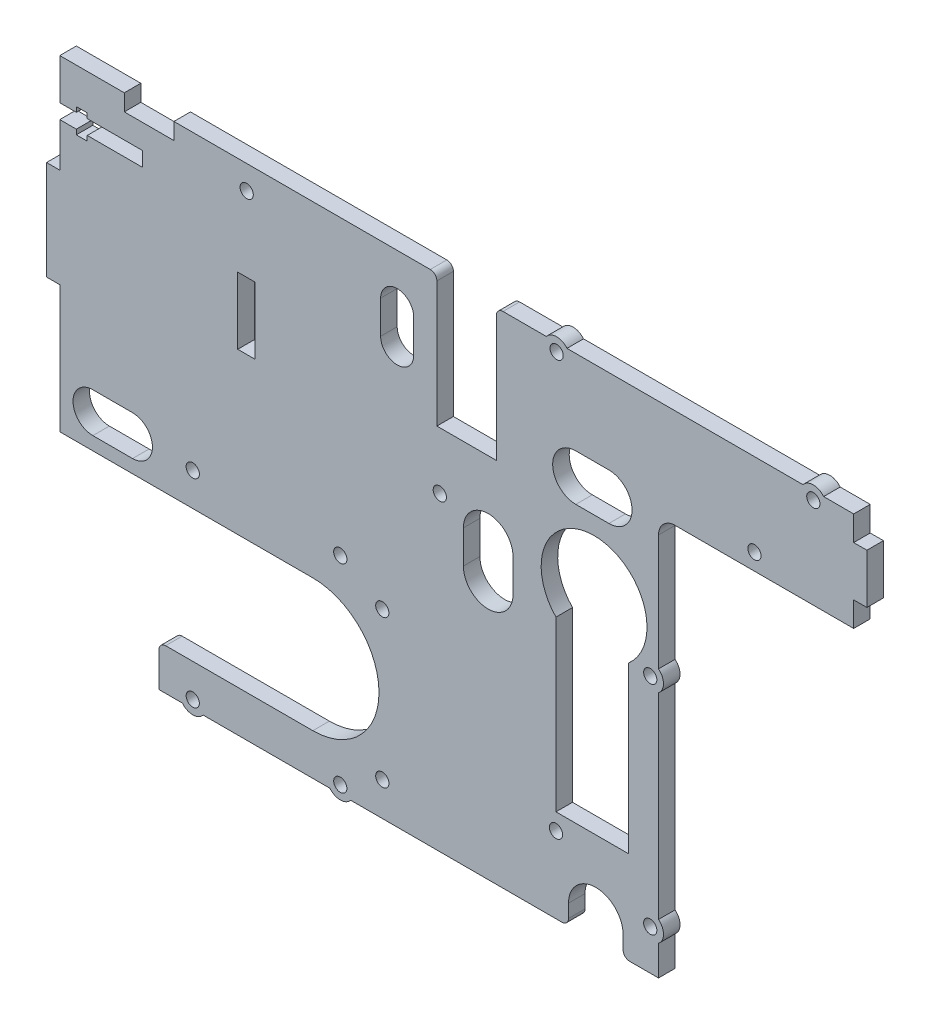
SolidWorks part; units mm, degrees
ref_plane "Front Plane" through (0, 0, 0) normal (0, 0, 1) x (1, 0, 0)
ref_plane "Top Plane" through (0, 0, 0) normal (0, 1, 0) x (1, 0, 0)
ref_plane "Right Plane" through (0, 0, 0) normal (1, 0, 0) x (0, 0, -1)
sketch "Sketch1" plane through (0, 0, 0) normal (0, 0, 1) x (1, 0, 0)
  line L1 (-120, 75.5) -> (120, 75.5)
  line L2 (-120, 75.5) -> (-120, -75.5)
  line L3 (-120, -75.5) -> (120, -75.5)
  line L4 (120, 75.5) -> (120, -75.5)
  dimension "D1" = 240
  dimension "D2" = 151
  dimension "D3" = 75.5
  dimension "D4" = 120
extrude "Boss-Extrude1" add sketch "Sketch1" along normal blind 5
sketch "Sketch5" plane through (0, 0, 0) normal (0, 0, -1) x (-1, 0, 0)
  line L0 (0, 0) -> (0, -52.2795) construction
  line L1 (0, 0) -> (58.5261, 0) construction
  line L3 (0, -43) -> (80.2371, -43) construction
  circle A1 centre (35.2, -73) radius 2
  circle A3 centre (79.8, -73) radius 2
  circle A5 centre (22.5, -65.3) radius 2
  circle A6 centre (22.5, -20.7) radius 2
  circle A7 centre (79.8, -13) radius 2
  circle A8 centre (35.2, -13) radius 2
  dimension "D5" = 44.6
  dimension "D6" = 4
  dimension "D7" = 4
  dimension "D8" = 4
  dimension "D1" = 22.5
  dimension "D2" = 65.3
  dimension "D3" = 35.2
  dimension "D4" = 73
  dimension "D9" = 43
extrude "Cut-Extrude1" cut sketch "Sketch5" against normal blind 5
sketch "Sketch6" plane through (0, 0, 0) normal (0, 0, -1) x (-1, 0, 0)
  circle A0 centre (35.2, -73) radius 2
  circle A1 centre (35.2, -73) radius 4
  circle A2 centre (79.8, -73) radius 2
  circle A3 centre (79.8, -73) radius 4
  dimension "D1" = 4
  dimension "D2" = 8
  dimension "D3" = 4
  dimension "D4" = 8
extrude "Boss-Extrude2" add sketch "Sketch6" against normal blind 5
sketch "Sketch7" plane through (0, 0, 0) normal (0, 0, -1) x (-1, 0, 0)
  line L0 (22.5, -63.3) -> (22.5, -22.7) construction
  line L1 (120, -63) -> (43.5, -63)
  line L2 (120, -63) -> (120, -23)
  line L3 (120, -23) -> (43.5, -23)
  line L6 (120, 75.5) -> (120, -75.5) construction
  line L7 (22.5, -43) -> (124.9489, -43) construction
  arc A1 (43.5, -23) -> (43.5, -63) centre (43.5, -43) ccw
  circle A2 centre (22.5, -65.3) radius 2 construction
  circle A3 centre (22.5, -20.7) radius 2 construction
  dimension "D2" = 40
  dimension "D3" = 76.5
extrude "Cut-Extrude2" cut sketch "Sketch7" against normal blind 5
sketch "Sketch8" plane through (0, 0, 0) normal (0, 0, -1) x (-1, 0, 0)
  line L0 (43.5, -63) -> (120, -63) construction
  line L1 (120, -75.5) -> (90, -75.5)
  line L2 (120, -75.5) -> (120, -63)
  line L3 (120, -63) -> (90, -63)
  line L4 (90, -75.5) -> (90, -63)
  point P7 (120, -69.25)
  dimension "D1" = 30
extrude "Cut-Extrude3" cut sketch "Sketch8" against normal blind 5
sketch "Sketch9" plane through (0, 0, 0) normal (0, 0, -1) x (-1, 0, 0)
  line L0 (-120, -75.5) -> (-120, 75.5) construction
  line L1 (-120, 45.5) -> (-61, 45.5)
  line L2 (-120, 45.5) -> (-120, -75.5)
  line L3 (-120, -75.5) -> (-61, -75.5)
  line L4 (-61, 45.5) -> (-61, -75.5)
  line L5 (-120, 75.5) -> (120, 75.5) construction
  line L6 (32.0775, -75.5) -> (-120, -75.5) construction
  dimension "D1" = 30
  dimension "D2" = 59
extrude "Cut-Extrude4" cut sketch "Sketch9" against normal blind 5
sketch "Sketch11" plane through (0, 0, 0) normal (0, 0, -1) x (-1, 0, 0)
  line L0 (50, 30) -> (30, 30) construction
  line L1 (50, 25) -> (30, 25)
  line L2 (50, 35) -> (30, 35)
  line L3 (0, 0) -> (24.3955, 0) construction
  arc A0 (50, 25) -> (50, 35) centre (50, 30) ccw
  arc A1 (30, 35) -> (30, 25) centre (30, 30) ccw
  point P2 (40, 30)
  dimension "D1" = 40
  dimension "D2" = 10
  dimension "D3" = 20
  dimension "D4" = 30
extrude "Cut-Extrude6" [suppressed] cut sketch "Sketch11" against normal blind 10
sketch "Sketch12" plane through (0, 0, 0) normal (0, 0, -1) x (-1, 0, 0)
  line L0 (-120, 75.5) -> (120, 75.5) construction
  line L1 (-12, 75.5) -> (6, 75.5)
  line L2 (-12, 75.5) -> (-12, 35.5)
  line L3 (-12, 35.5) -> (6, 35.5)
  line L4 (6, 75.5) -> (6, 35.5)
  line L5 (-120, 45.5) -> (-120, 75.5) construction
  dimension "D1" = 108
  dimension "D2" = 40
  dimension "D3" = 18
extrude "Cut-Extrude7" cut sketch "Sketch12" against normal blind 10
sketch "Sketch15" plane through (0, 0, 5) normal (0, 0, 1) x (1, 0, 0)
  line L1 (0, 0) -> (0, 47.824) construction
  line L3 (0, 0) -> (-48.3732, 0) construction
  circle A1 centre (-63.5, 68.3) radius 2
  dimension "D2" = 4
extrude "Cut-Extrude9" cut sketch "Sketch15" against normal blind 5
sketch "Sketch16" plane through (0, 0, 0) normal (0, 0, -1) x (-1, 0, 0)
  line L8 (66.2, 25.5) -> (66.2, 45.7)
  line L9 (66.2, 45.7) -> (61, 45.7)
  line L10 (61, 45.7) -> (61, 25.5)
  line L11 (61, 25.5) -> (66.2, 25.5)
  dimension "D1" = 5.2
  dimension "D2" = 20.2
extrude "Cut-Extrude10" cut sketch "Sketch16" against normal blind 5
sketch "Sketch18" plane through (0, 0, 0) normal (0, 0, -1) x (-1, 0, 0)
  line L0 (-9.507, 12.8501) -> (-9.507, 2.8501) construction
  line L1 (-2.007, 12.8501) -> (-2.007, 2.8501)
  line L2 (-17.007, 12.8501) -> (-17.007, 2.8501)
  line L3 (32.0775, -75.5) -> (-61, -75.5) construction
  arc A0 (-2.007, 12.8501) -> (-17.007, 12.8501) centre (-9.507, 12.8501) ccw
  arc A1 (-17.007, 2.8501) -> (-2.007, 2.8501) centre (-9.507, 2.8501) ccw
  point P2 (-9.507, 7.8501)
  dimension "D1" = 15
  dimension "D2" = 10
  dimension "D3" = 83.3501
extrude "Cut-Extrude11" cut sketch "Sketch18" against normal blind 10
sketch "Sketch19" plane through (0, 0, 0) normal (0, 0, -1) x (-1, 0, 0)
  circle A1 centre (-38.2956, 10.1034) radius 15
  dimension "D1" = 30
extrude "Cut-Extrude12" [suppressed] cut sketch "Sketch19" against normal blind 10
sketch "Sketch20" plane through (0, 0, 0) normal (0, 0, -1) x (-1, 0, 0)
  line L0 (-50.2956, -69.5) -> (-50.2956, -75.5)
  line L1 (32.0775, -75.5) -> (-61, -75.5) construction
  line L2 (-33.7956, -69.5) -> (-33.7956, -75.5)
  line L3 (-61, -75.5) -> (-61, 45.5) construction
  arc A1 (-33.7956, -69.5) -> (-50.2956, -69.5) centre (-42.0456, -69.5) ccw
  line M25 (-61, -75.5) -> (32.0775, -75.5)
  dimension "D1" = 16.5
  dimension "D2" = 10.7044
  dimension "D3" = 6
extrude "Cut-Extrude13" cut sketch "Sketch20" against normal blind 10 and the other way through all contours L2 A1 L0 M25
sketch "Sketch21" plane through (0, 0, 0) normal (0, 0, -1) x (-1, 0, 0)
  line L0 (-30.5615, -47.8466) -> (-23.1175, -54.6727)
  line L1 (-23.1175, -54.6727) -> (-26.5644, -58.4316)
  line L2 (-26.5644, -58.4316) -> (-34.0084, -51.6054)
  line L3 (-34.0084, -51.6054) -> (-30.5615, -47.8466)
  dimension "D1" = 10.1
  dimension "D2" = 5.1
extrude "Cut-Extrude14" [suppressed] cut sketch "Sketch21" against normal blind 10
sketch "Sketch22" plane through (0, 0, 0) normal (0, 0, -1) x (-1, 0, 0)
  circle A0 centre (1.8314, 16.7591) radius 2
  circle A1 centre (39.5923, 57.5693) radius 2
  dimension "D1" = 4
  dimension "D2" = 4
extrude "Cut-Extrude15" [suppressed] cut sketch "Sketch22" against normal blind 10
sketch "Sketch23" plane through (0, 0, 0) normal (0, 0, -1) x (-1, 0, 0)
  circle A0 centre (-107.8, 73) radius 2
  circle A1 centre (-30.2, 73) radius 2
  dimension "D1" = 4
  dimension "D2" = 4
extrude "Cut-Extrude16" cut sketch "Sketch23" against normal blind 5
sketch "Sketch24" plane through (0, 0, 0) normal (0, 0, -1) x (-1, 0, 0)
  circle A0 centre (-107.8, 73) radius 2
  circle A1 centre (-107.8, 73) radius 4
  circle A2 centre (-30.2, 73) radius 2
  circle A3 centre (-30.2, 73) radius 4
  dimension "D1" = 8
  dimension "D2" = 8
extrude "Boss-Extrude4" add sketch "Sketch24" against normal blind 5
sketch "Sketch25" plane through (0, 0, 0) normal (0, 0, -1) x (-1, 0, 0)
  circle A0 centre (117.5, 7.7) radius 2
  circle A1 centre (117.5, 63.3) radius 2
  dimension "D1" = 4
  dimension "D2" = 4
extrude "Cut-Extrude17" [suppressed] cut sketch "Sketch25" against normal blind 5
sketch "Sketch26" [suppressed] plane through (0, 0, 0) normal (0, 0, -1) x (-1, 0, 0)
  circle A0 centre (117.5, 63.3) radius 2
  circle A1 centre (117.5, 63.3) radius 4
  circle A2 centre (117.5, 7.7) radius 2
  circle A3 centre (117.5, 7.7) radius 4
  dimension "D1" = 8
  dimension "D2" = 4
  dimension "D3" = 8
extrude "Boss-Extrude5" [suppressed] add sketch "Sketch26" against normal blind 5
sketch "Sketch27" plane through (0, 0, 0) normal (0, 0, -1) x (-1, 0, 0)
  line L0 (120, -23) -> (43.5, -23) construction
  line L1 (120, 75.5) -> (120, -23) construction
  line L2 (6, 75.5) -> (120, 75.5) construction
  circle A0 centre (90, -13) radius 2
  circle A1 centre (90, 65.5) radius 2
  dimension "D1" = 4
  dimension "D3" = 30
  dimension "D5" = 4
  dimension "D2" = 10
  dimension "D4" = 10
extrude "Cut-Extrude18" [suppressed] cut sketch "Sketch27" against normal blind 10
sketch "Sketch30" plane through (0, 0, 0) normal (0, 0, -1) x (-1, 0, 0)
  line L0 (110, -13) -> (98, -13) construction
  line L1 (110, -19) -> (98, -19)
  line L2 (110, -7) -> (98, -7)
  line L3 (120, 75.5) -> (120, -23) construction
  line L5 (120, -23) -> (43.5, -23) construction
  arc A0 (110, -19) -> (110, -7) centre (110, -13) ccw
  arc A1 (98, -7) -> (98, -19) centre (98, -13) ccw
  point P3 (104, -13)
  dimension "D1" = 10
  dimension "D2" = 12
  dimension "D3" = 10
  dimension "D4" = 12
extrude "Cut-Extrude19" cut sketch "Sketch30" against normal blind 10
sketch "Sketch32" plane through (0, 0, 0) normal (0, 0, -1) x (-1, 0, 0)
  line L0 (120, 75.5) -> (120, -23) construction
  line L1 (120, 45.5) -> (124, 45.5)
  line L2 (120, 45.5) -> (120, 15.5)
  line L3 (120, 15.5) -> (124, 15.5)
  line L4 (124, 45.5) -> (124, 15.5)
  line L5 (6, 75.5) -> (120, 75.5) construction
  line L6 (-120, 45.5) -> (-120, 75.5) construction
  line L7 (-120, 53) -> (-124, 53)
  line L8 (-120, 53) -> (-120, 68)
  line L9 (-120, 68) -> (-124, 68)
  line L10 (-124, 53) -> (-124, 68)
  line L11 (-120, 75.5) -> (-110.9225, 75.5) construction
  line L12 (-61, 45.5) -> (-120, 45.5) construction
  dimension "D1" = 4
  dimension "D2" = 30
  dimension "D3" = 30
  dimension "D4" = 7.5
  dimension "D5" = 7.5
  dimension "D6" = 4
extrude "Boss-Extrude6" add sketch "Sketch32" against normal blind 5
fillet "Fillet1" radius 5 1 edges at (61, 45.5, 2.5)
sketch "Sketch33" plane through (0, 0, 0) normal (0, 0, -1) x (-1, 0, 0)
  line L0 (33.5752, 62.5315) -> (19.4077, 46.1983) construction
  line L1 (38.0015, 58.6921) -> (23.8341, 42.3588)
  line L2 (29.1488, 66.3709) -> (14.9814, 50.0377)
  arc A0 (38.0015, 58.6921) -> (29.1488, 66.3709) centre (33.5752, 62.5315) ccw
  arc A1 (14.9814, 50.0377) -> (23.8341, 42.3588) centre (19.4077, 46.1983) ccw
  point P2 (26.4914, 54.3649)
extrude "Cut-Extrude21" [suppressed] cut sketch "Sketch33" against normal blind 5
fillet "Fillet2" radius 2 5 edges at (-90, -63, 2.5) (50.2956, -75.5, 2.5) (33.7956, -75.5, 2.5) (12, 75.5, 2.5) (-6, 75.5, 2.5)
sketch "Sketch34" plane through (0, 0, 0) normal (0, 0, -1) x (-1, 0, 0)
  line L0 (90.9251, 60.9367) -> (120.7978, 60.9367) construction
  line L14 (0, 0) -> (0, 50.6952) construction
  line L16 (115, 58.7367) -> (120, 58.7367)
  line L17 (115, 57.2367) -> (115, 58.7367)
  line L18 (111.7, 57.2367) -> (115, 57.2367)
  line L19 (111.7, 58.7367) -> (111.7, 57.2367)
  line L20 (95, 58.7367) -> (111.7, 58.7367)
  line L21 (95, 63.1367) -> (95, 58.7367)
  line L22 (111.7, 63.1367) -> (95, 63.1367)
  line L23 (111.7, 64.6367) -> (111.7, 63.1367)
  line L24 (115, 64.6367) -> (111.7, 64.6367)
  line L25 (115, 63.1367) -> (115, 64.6367)
  line L26 (120, 63.1367) -> (115, 63.1367)
  line L27 (120, 58.7367) -> (120, 63.1367)
extrude "Cut-Extrude22" cut sketch "Sketch34" against normal blind 5
sketch "Sketch35" plane through (0, 0, 0) normal (0, 0, -1) x (-1, 0, 0)
  circle A1 centre (-38.2956, -38.9784) radius 10
  dimension "D1" = 20
extrude "Cut-Extrude23" [suppressed] cut sketch "Sketch35" against normal blind 5
sketch "Sketch36" plane through (0, 0, 0) normal (0, 0, -1) x (-1, 0, 0)
  line L0 (-61, -75.5) -> (-61, 40.5) construction
  circle A1 centre (-33, -53.4404) radius 2
  dimension "D1" = 28
extrude "Cut-Extrude24" [suppressed] cut sketch "Sketch36" against normal blind 5
sketch "Sketch37" plane through (0, 0, 0) normal (0, 0, -1) x (-1, 0, 0)
  line L0 (-61, -75.5) -> (-61, 40.5) construction
  line L2 (32.0775, -75.5) -> (-31.7956, -75.5) construction
  circle A0 centre (-30, -52.5) radius 2
  dimension "D2" = 4
  dimension "D3" = 31
  dimension "D5" = 23
extrude "Cut-Extrude25" cut sketch "Sketch37" against normal blind 10
sketch "Sketch38" plane through (0, 0, 0) normal (0, 0, -1) x (-1, 0, 0)
  circle A0 centre (5.1152, 18.2667) radius 2
  dimension "D1" = 4
extrude "Cut-Extrude26" cut sketch "Sketch38" against normal blind 10
sketch "Sketch39" plane through (0, 0, 0) normal (0, 0, -1) x (-1, 0, 0)
  line L1 (92.5, 16.25) -> (87.5, 16.25)
  line L3 (92.5, 36.25) -> (87.5, 36.25)
  line L5 (92.5, 16.25) -> (92.5, 36.25)
  line L7 (87.5, 16.25) -> (87.5, 36.25)
extrude "Cut-Extrude27" [suppressed] cut sketch "Sketch39" against normal blind 5
sketch "Sketch42" plane through (0, 0, 0) normal (0, 0, -1) x (-1, 0, 0)
  line L1 (-52, -47.5) -> (-52, 2.5)
  line L3 (-30, -47.5) -> (-30, 3.4862)
  line L5 (-30, -47.5) -> (-52, -47.5)
  line L6 (-61, -75.5) -> (-61, 40.5) construction
  line L7 (32.0775, -75.5) -> (-31.7956, -75.5) construction
  arc A1 (-30, 3.4862) -> (-52, 2.5) centre (-41.5199, 14.5899) ccw
  dimension "D3" = 16
  dimension "D1" = 9
  dimension "D2" = 22
  dimension "D4" = 50
  dimension "D5" = 28
extrude "Cut-Extrude29" cut sketch "Sketch42" against normal blind 10
sketch "Sketch43" plane through (0, 0, 0) normal (0, 0, -1) x (-1, 0, 0)
  circle A0 centre (-58.5, 2.3) radius 2
  circle A1 centre (-58.5, -63.3) radius 2
  dimension "D1" = 4
  dimension "D2" = 4
extrude "Cut-Extrude30" cut sketch "Sketch43" against normal blind 10
sketch "Sketch44" plane through (0, 0, 0) normal (0, 0, -1) x (-1, 0, 0)
  circle A0 centre (-58.5, 2.3) radius 2
  circle A1 centre (-58.5, 2.3) radius 4
  circle A2 centre (-58.5, -63.3) radius 2
  circle A3 centre (-58.5, -63.3) radius 4
  dimension "D1" = 8
  dimension "D2" = 8
extrude "Boss-Extrude7" add sketch "Sketch44" against normal blind 5
sketch "Sketch45" plane through (0, 0, 0) normal (0, 0, -1) x (-1, 0, 0)
  line L0 (18, 60.5) -> (18, 50.5) construction
  line L1 (23, 60.5) -> (23, 50.5)
  line L2 (13, 60.5) -> (13, 50.5)
  line L3 (6, 35.5) -> (6, 73.5) construction
  line L4 (8, 75.5) -> (120, 75.5) construction
  arc A0 (23, 60.5) -> (13, 60.5) centre (18, 60.5) ccw
  arc A1 (13, 50.5) -> (23, 50.5) centre (18, 50.5) ccw
  point P2 (18, 55.5)
  dimension "D3" = 10
  dimension "D1" = 7
  dimension "D2" = 10
  dimension "D4" = 15
extrude "Cut-Extrude31" cut sketch "Sketch45" against normal blind 10
sketch "Sketch46" plane through (0, 0, 0) normal (0, 0, -1) x (-1, 0, 0)
  line L0 (-46, 43) -> (-36, 43) construction
  line L1 (-46, 50) -> (-36, 50)
  line L2 (-46, 36) -> (-36, 36)
  line L3 (-61, 5.4225) -> (-61, 40.5) construction
  arc A0 (-46, 50) -> (-46, 36) centre (-46, 43) ccw
  arc A1 (-36, 36) -> (-36, 50) centre (-36, 43) ccw
  point P2 (-41, 43)
  dimension "D1" = 20
  dimension "D2" = 43
  dimension "D3" = 7
  dimension "D4" = 10
extrude "Cut-Extrude32" cut sketch "Sketch46" against normal blind 10
sketch "Sketch47" plane through (0, 0, 0) normal (0, 0, -1) x (-1, 0, 0)
  line L0 (-66, 45.5) -> (-120, 45.5) construction
  line L1 (-120, 45.5) -> (-120, 53) construction
  circle A0 centre (-90, 50.5) radius 2
  dimension "D1" = 4
  dimension "D3" = 30
  dimension "D2" = 5
extrude "Cut-Extrude33" cut sketch "Sketch47" against normal blind 10
sketch "Sketch48" plane through (0, 0, 0) normal (0, 0, -1) x (-1, 0, 0)
  line L4 (85.5, 75.5) -> (100.5, 75.5)
  line L5 (85.5, 70.5) -> (85.5, 75.5)
  line L6 (100.5, 70.5) -> (100.5, 75.5)
  line L7 (85.5, 70.5) -> (100.5, 70.5)
extrude "Cut-Extrude34" cut sketch "Sketch48" against normal blind 5
